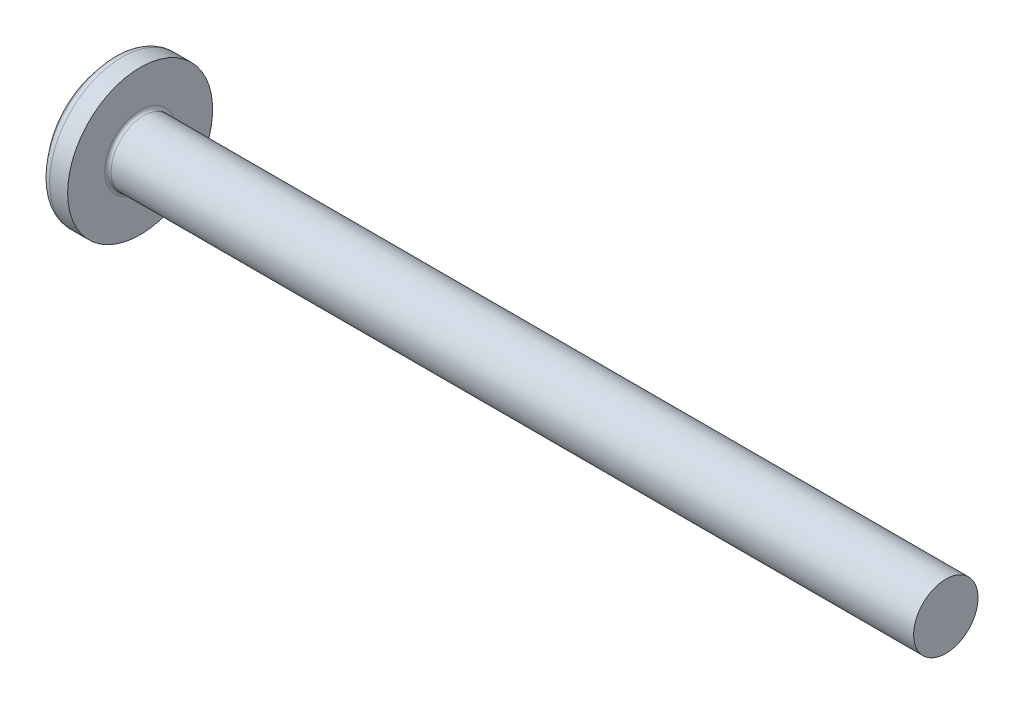
SolidWorks part; units mm, degrees
material "普通碳钢"
ref_plane "Plane1" through (0, 0, 0) normal (0, 0, 1) x (1, 0, 0)
ref_plane "Plane2" through (0, 0, 0) normal (0, 1, 0) x (1, 0, 0)
ref_plane "Plane3" through (0, 0, 0) normal (1, 0, 0) x (0, 0, -1)
sketch "BodySke" plane through (0, 0, 0) normal (0, 0, 1) x (1, 0, 0)
  line L0 (1.6, 1) -> (1.6, 2.25)
  line L2 (-25.4, 0) -> (127, 0) construction
  line L3 (26.6, 0) -> (0, 0)
  line L4 (1.6, 1) -> (26.6, 1)
  line L5 (26.6, 1) -> (26.6, 0)
  line L6 (1.0403, 2.25) -> (1.6, 2.25)
  arc A0 (0.8412, 2.1625) -> (0, 0) centre (3.2, 0) ccw
  arc A2 (0.8412, 2.1625) -> (1.0403, 2.25) centre (1.0403, 1.98) cw
  dimension "Head_fillet_rad" = 0.27
  dimension "Head_crown_rad" = 3.2
  dimension "D1" = 25
  dimension "Head_ht" = 1.6
  dimension "Diameter" = 2
  dimension "Head_dia" = 4.5
revolve "Base-Revolve" add sketch "BodySke"
cosmetic thread "ThreadCosmetic" [suppressed]
fillet "Fillet1" radius 0.1 1 edges at (1.6, 0, 1)
sketch "Sketch3" plane through (0, 0, 0) normal (1, 0, 0) x (0, 0, -1)
  line L0 (0.37, -0.95) -> (-0.37, -0.95)
  line L1 (0.37, -0.95) -> (0.37, 0.95)
  line L2 (-0.37, 0.95) -> (0.37, 0.95)
  line L3 (-0.37, 0.95) -> (-0.37, -0.95)
  dimension "D1" = 0.95
  dimension "Cross_dia" = 1.9
  dimension "D2" = 0.37
  dimension "Cross_width" = 0.74
ref_plane "Plane4" through (1.75, 0, 0) normal (1, 0, 0) x (0, 0, -1)
sketch "Sketch4" plane through (1.75, 0, 0) normal (1, 0, 0) x (0, 0, -1)
  line L0 (0.37, -0.5275) -> (-0.37, -0.5275)
  line L1 (0.37, -0.5275) -> (0.37, 0.5275)
  line L2 (-0.37, 0.5275) -> (0.37, 0.5275)
  line L3 (-0.37, 0.5275) -> (-0.37, -0.5275)
  dimension "D1" = 0.74
  dimension "D2" = 1.055
  dimension "D3" = 0.37
  dimension "D4" = 0.5275
loft "Recess" cut profiles "Sketch3", "Sketch4"
pattern_circular "RecPat" count 2 every 90 about axis through (0, 0, 0) along (1, 0, 0) of "Recess"
sketch "RecCorSke" plane through (0, 0, 0) normal (0, 0, 1) x (1, 0, 0)
  line L0 (-3.175, 0) -> (15.875, 0) construction
  line L1 (-25.4, 0) -> (127, 0) construction
  line L2 (0, 0) -> (0, 0.6784)
  line L3 (0, 0.6784) -> (1.75, 0.556)
  line L4 (1.75, 0.556) -> (1.9307, 0)
  line L5 (1.9307, 0) -> (0, 0)
  dimension "Diameter" = 1.112
  dimension "Depth" = 1.75
  dimension "Draft_angle" = 4
  dimension "Bottom_angle" = 18
revolve "RecessCore" cut sketch "RecCorSke" angle 360 about L0
